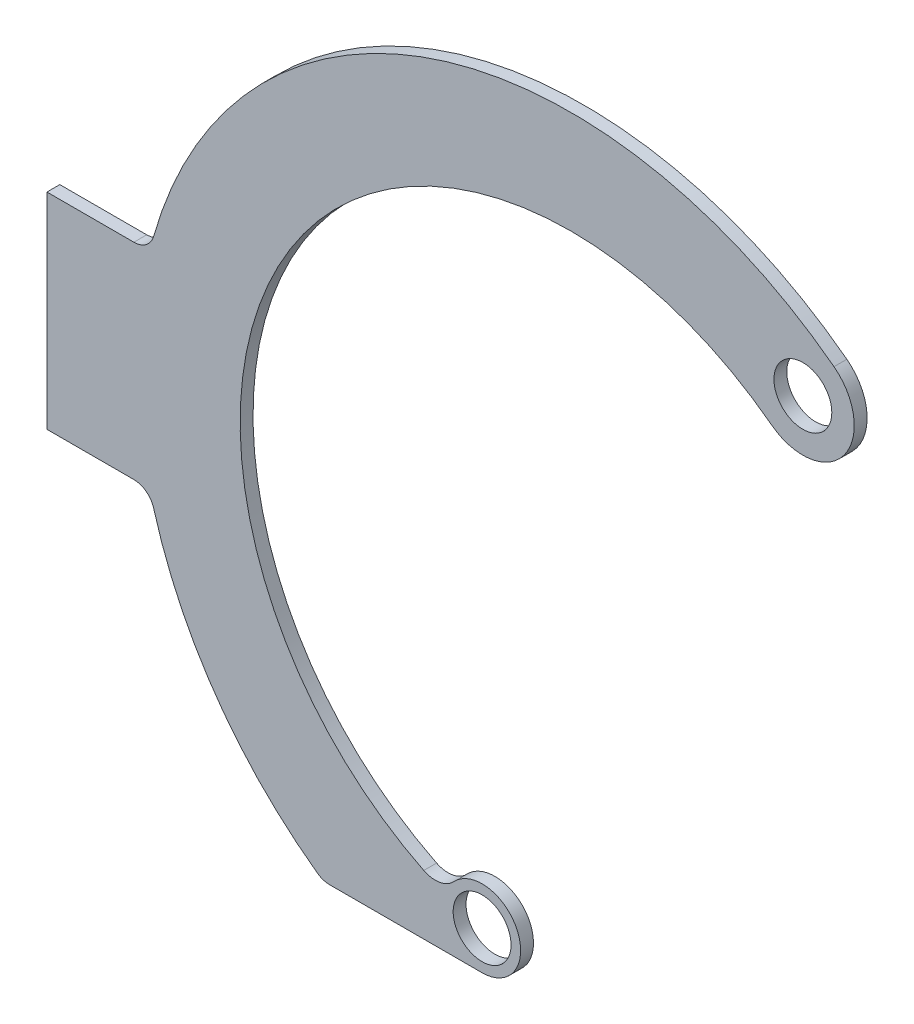
SolidWorks part; units mm, degrees
ref_plane "Front Plane" through (0, 0, 0) normal (0, 0, 1) x (1, 0, 0)
ref_plane "Top Plane" through (0, 0, 0) normal (0, 1, 0) x (1, 0, 0)
ref_plane "Right Plane" through (0, 0, 0) normal (1, 0, 0) x (0, 0, -1)
sketch "Sketch1" plane through (0, 0, 0) normal (0, 0, 1) x (1, 0, 0)
  line L0 (-230.8876, -29.4) -> (49769.1124, -29.4) construction
  line L9 (0, 0) -> (75.7447, 146.7383) construction
  line L10 (75.7447, 146.7383) -> (158.5474, 307.15) construction
  line L11 (44.0107, 156.8115) -> (158.5474, 307.15) construction
  line L12 (-101.3625, 231.8515) -> (25.5961, 166.3169) construction
  line L13 (-101.3625, 231.8515) -> (-209.2776, 22.7902) construction
  line L14 (158.5474, 307.15) -> (135.977, 318.8006) construction
  line L15 (158.5474, 307.15) -> (181.1178, 295.4994) construction
  line L16 (0, -19.05) -> (-78.6242, -19.05)
  line L19 (-215.0822, 207.6115) -> (-164.2822, 207.6115)
  line L20 (-215.0822, 207.6115) -> (-215.0822, 106.0115)
  line L21 (-215.0822, 106.0115) -> (-164.2822, 106.0115)
  line L22 (-164.2822, 207.6115) -> (-164.2822, 106.0115)
  line L23 (-215.0822, 207.6115) -> (-164.2822, 106.0115) construction
  line L24 (-215.0822, 106.0115) -> (-164.2822, 207.6115) construction
  circle A0 centre (0, 0) radius 25.4 construction
  circle A1 centre (158.5474, 307.15) radius 50.8 construction
  arc A3 (143.1545, 286.9456) -> (-18.2336, 5.517) centre (44.0107, 156.8115) ccw
  circle A5 centre (158.5474, 307.15) radius 14.3002
  circle A6 centre (158.5474, 307.15) radius 25.4
  arc A8 (192.5214, 311.4438) -> (-78.6242, -19.05) centre (44.0107, 156.8115) ccw
  arc A9 (181.1178, 295.4994) -> (192.5214, 311.4438) centre (185.6608, 304.3004) ccw
  circle A11 centre (0, 0) radius 14.3002
  circle A12 centre (0, 0) radius 19.05
  circle A15 centre (25.5961, 166.3169) radius 142.875 construction
  point P10 (0, 0)
  point P11 (101.7912, 229.431)
  point P12 (0, 0)
  point P18 (-16.1818, 10.0525)
  point P19 (26.2302, 137.2154)
  point P21 (-156.5866, 127.3508)
  point P36 (-189.6822, 156.8115)
  dimension "D1" = 50.8
  dimension "D11" = 28.6004
  dimension "D12" = 50.8
  dimension "D5" = 101.6
  dimension "D7" = 38.1
  dimension "D4" = 285.75
  dimension "D13" = 90
  dimension "D15" = 50.8
  dimension "D16" = 101.6
  dimension "D2" = 4
  dimension "D3" = 285.75
  dimension "D6" = 10
  dimension "D8" = 50.8
extrude "Boss-Extrude1" add sketch "Sketch1" along normal blind 6.35
fillet "Fillet1" radius 10.16 3 edges at (-78.6242, -19.05, 3.175) (-164.2822, 106.0115, 3.175) (-164.2822, 207.6115, 3.175)
fillet "Fillet2" radius 12.7 1 edges at (-18.2336, 5.517, 3.175)
equation "\"balldiam\"= 11.25"
equation "\"D4@Sketch1\"=\"balldiam\""
equation "\"D3@Sketch1\"=\"balldiam\""
